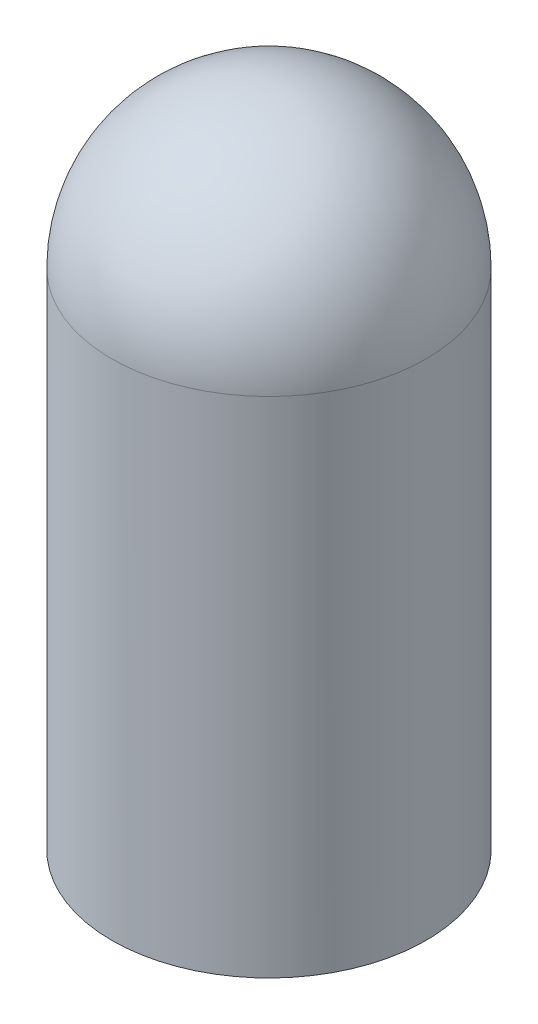
SolidWorks part; units mm, degrees
ref_plane "Front Plane" through (0, 0, 0) normal (0, 0, 1) x (1, 0, 0)
ref_plane "Top Plane" through (0, 0, 0) normal (0, 1, 0) x (1, 0, 0)
ref_plane "Right Plane" through (0, 0, 0) normal (1, 0, 0) x (0, 0, -1)
sketch "Sketch1" plane through (0, 0, 0) normal (0, 0, 1) x (1, 0, 0)
  line L0 (9.75, 0) -> (9.75, 31.25)
  line L1 (9.75, 0) -> (0, 0)
  line L2 (0, 0) -> (0, 31.25)
  line L3 (0, 31.25) -> (0, 41)
  arc A0 (9.75, 31.25) -> (0, 41) centre (0, 31.25) ccw
  dimension "D1" = 31.25
  dimension "D2" = 9.75
revolve "Revolve1" add sketch "Sketch1" angle 360 about L2
shell "Shell1" thickness 0.5
